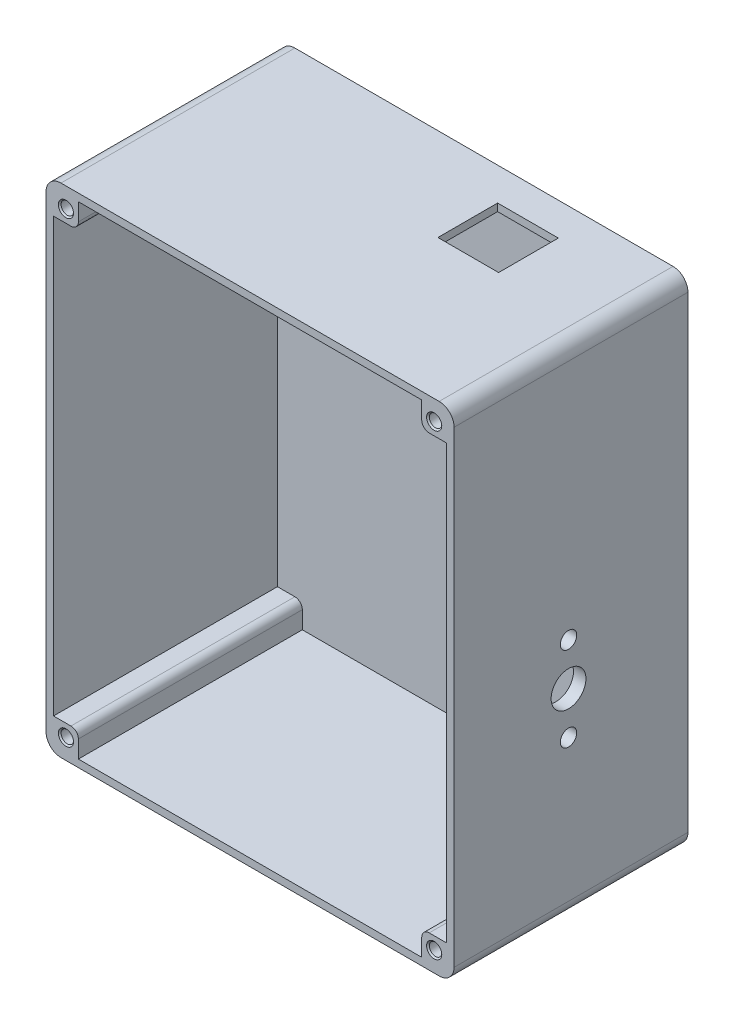
SolidWorks part; units mm, degrees
ref_plane "前视基准面" through (0, 0, 0) normal (0, 0, 1) x (1, 0, 0)
ref_plane "上视基准面" through (0, 0, 0) normal (0, 1, 0) x (1, 0, 0)
ref_plane "右视基准面" through (0, 0, 0) normal (1, 0, 0) x (0, 0, -1)
other "Configuration Table"
sketch "草图2" plane through (0, 0, 0) normal (0, 0, 1) x (1, 0, 0)
  line L1 (0, 0) -> (82, 0)
  line L2 (0, 0) -> (0, -100)
  line L3 (0, -100) -> (82, -100)
  line L4 (82, 0) -> (82, -100)
  dimension "D1" = 82
  dimension "D2" = 100
extrude "凸台-拉伸1" add sketch "草图2" along normal blind 2
sketch "草图9" plane through (0, 0, 2) normal (0, 0, 1) x (1, 0, 0)
  line L0 (0, -50) -> (82, -50) construction
  line L3 (80.5, -6.5) -> (75.5, -6.5)
  line L4 (0, 0) -> (82, 0) construction
  line L5 (82, 0) -> (82, -100) construction
  line L6 (0, -100) -> (82, -100) construction
  line L7 (0, 0) -> (0, -100) construction
  line L8 (80.5, -98.5) -> (80.5, -1.5)
  line L9 (80.5, -1.5) -> (1.5, -1.5)
  line L10 (1.5, -1.5) -> (1.5, -98.5)
  line L11 (1.5, -98.5) -> (80.5, -98.5)
  line L12 (80.5, -93.5) -> (80.5, -6.5)
  line L13 (75.5, -1.5) -> (6.5, -1.5)
  line L14 (1.5, -6.5) -> (1.5, -93.5)
  line L15 (6.5, -98.5) -> (75.5, -98.5)
  line L16 (0, 0) -> (82, 0)
  line L17 (82, 0) -> (82, -100)
  line L18 (0, -100) -> (82, -100)
  line L19 (0, 0) -> (0, -100)
  line L20 (75.5, -1.5) -> (75.5, -6.5)
  line L23 (1.5, -6.5) -> (6.5, -6.5)
  line L24 (6.5, -1.5) -> (6.5, -6.5)
  line L25 (75.5, -98.5) -> (75.5, -93.5)
  line L26 (80.5, -93.5) -> (75.5, -93.5)
  line L27 (6.5, -98.5) -> (6.5, -93.5)
  line L28 (1.5, -93.5) -> (6.5, -93.5)
  dimension "D2" = 5
  dimension "D3" = 5
  dimension "D4" = 5
  dimension "D5" = 5
  dimension "D1" = 1.5
extrude "凸台-拉伸4" add sketch "草图9" along normal blind 45
sketch "草图10" plane through (0, 0, 2) normal (0, 0, 1) x (1, 0, 0)
  line L0 (15, -6) -> (67, -6) construction
  line L1 (75.5, -1.5) -> (6.5, -1.5) construction
  line L2 (75.5, -1.5) -> (6.5, -1.5) construction
  circle A0 centre (15, -6) radius 2.25
  circle A1 centre (67, -6) radius 2.25
  circle A2 centre (67, -38) radius 2.25
  circle A3 centre (15, -38) radius 2.25
  point P2 (41, -6)
  point P11 (41, -1.5)
  dimension "D1" = 4.5
  dimension "D2" = 2
  dimension "D4" = 52
  dimension "D5" = 32
  dimension "D6" = 4.5
  dimension "D3" = 2
extrude "凸台-拉伸5" add sketch "草图10" along normal blind 3
sketch "草图11" plane through (0, 0, 5) normal (0, 0, 1) x (1, 0, 0)
  circle A0 centre (67, -6) radius 2.25 construction
  circle A1 centre (67, -38) radius 2.25 construction
  circle A2 centre (15, -38) radius 2.25 construction
  circle A3 centre (15, -6) radius 2.25 construction
  circle A4 centre (67, -6) radius 2.25
  circle A5 centre (67, -38) radius 2.25
  circle A6 centre (15, -38) radius 2.25
  circle A7 centre (15, -6) radius 2.25
  circle A8 centre (15, -6) radius 1.25
  circle A9 centre (67, -6) radius 1.25
  circle A10 centre (67, -38) radius 1.25
  circle A11 centre (15, -38) radius 1.25
  point P0 (67, -6)
  point P2 (67, -38)
  point P4 (15, -38)
  point P6 (15, -6)
  dimension "D1" = 1
hole_wizard "M3 Tapped Hole1" positions "草图11" profile "草图13" tap size "M3" standard "GB" end condition up to next
cosmetic thread "孔螺纹线1" parameters "D2"=3
cosmetic thread "孔螺纹线2" parameters "D2"=3
cosmetic thread "孔螺纹线3" parameters "D2"=3
cosmetic thread "孔螺纹线4" parameters "D2"=3
sketch "草图13" plane through (67, -6, 5) normal (1, 0, 0) x (0, -1, 0)
  line L0 (0, 0) -> (0, 5)
  line L1 (0, 5) -> (1.25, 5)
  line L2 (1.25, 5) -> (1.25, 0.275)
  line L3 (1.25, 0.275) -> (1.525, 0)
  line L5 (1.525, 0) -> (0, 0)
  line L6 (-1.25, 0.275) -> (-1.525, 0) construction
  line L11 (0, -6.35) -> (0, 107.95) construction
  dimension "Thru Tap Drill Dia." = 2.5
  dimension "Thru Tap Drill Depth" = 5
  dimension "Near C'Sink Dia." = 3.05
  dimension "Near C'Sink Angle" = 90
ref_point "点2"
sketch "草图14" plane through (0, -1.5, 0) normal (0, -1, 0) x (1, 0, 0)
  line L0 (67, 5) -> (67, 23.1936) construction
  line L1 (62.55, 6.6) -> (50.35, 6.6)
  line L2 (62.55, 6.6) -> (62.55, 18.6)
  line L3 (62.55, 18.6) -> (50.35, 18.6)
  line L4 (50.35, 6.6) -> (50.35, 18.6)
  dimension "D1" = 12.2
  dimension "D2" = 12
  dimension "D3" = 4.45
  dimension "D4" = 1.6
extrude "切除-拉伸2" cut sketch "草图14" against normal up to next
sketch "草图16" plane through (82, 0, 0) normal (1, 0, 0) x (0, 0, -1)
  line L0 (-24, -49.191) -> (-24, -71.8515) construction
  line L2 (-30.5809, -60) -> (-18.6896, -60) construction
  line L3 (0, 0) -> (0, -100) construction
  line L4 (-47, 0) -> (0, 0) construction
  circle A0 centre (-24, -60) radius 3.5
  circle A1 centre (-24, -51.5) radius 1.65
  circle A2 centre (-24, -68.5) radius 1.65
  point P5 (-24, -60)
  dimension "D1" = 7
  dimension "D3" = 3.3
  dimension "D4" = 24
  dimension "D2" = 8.5
  dimension "D5" = 60
extrude "切除-拉伸3" cut sketch "草图16" against normal up to next
sketch "草图17" plane through (80.5, 0, 0) normal (-1, 0, 0) x (0, 0, 1)
  line L1 (11, -47) -> (37, -47)
  line L2 (11, -47) -> (11, -73)
  line L3 (11, -73) -> (37, -73)
  line L4 (37, -47) -> (37, -73)
  circle A0 centre (24, -68.5) radius 1.65 construction
  circle A1 centre (24, -60) radius 3.5 construction
  circle A2 centre (24, -51.5) radius 1.65 construction
  circle A3 centre (24, -68.5) radius 1.65
  circle A4 centre (24, -60) radius 3.5
  circle A5 centre (24, -51.5) radius 1.65
  point P13 (37, -60)
  point P15 (24, -60)
  point P16 (24, -47)
  point P17 (24, -51.5)
  circle M2 centre (24, -68.5) radius 1.65
  circle M3 centre (24, -51.5) radius 1.65
  circle M4 centre (24, -60) radius 3.5
  dimension "D1" = 26
  dimension "D2" = 26
extrude "凸台-拉伸6" add sketch "草图17" along normal blind 1 contours L4 L1 L2 L3 M3 M4 M2
sketch "草图20" plane through (0, 0, 47) normal (0, 0, 1) x (1, 0, 0)
  line L10 (0, 0) -> (0, -100) construction
  line L11 (6.5, -6.5) -> (1.5, -6.5) construction
  line L15 (0, -100) -> (82, -100) construction
  point P4 (4, -4)
  point P23 (4, -96)
  point P28 (78, -96)
  point P29 (78, -4)
  dimension "D1" = 4
  dimension "D2" = 2.5
  dimension "D3" = 4
  dimension "D4" = 74
hole_wizard "M3 Tapped Hole3" positions "草图20" profile "草图24" tap size "M3" standard "GB" end condition up to next
sketch "草图24" plane through (4, -4, 47) normal (1, 0, 0) x (0, -1, 0)
  line L0 (0, 0) -> (0, 47)
  line L1 (0, 47) -> (1.25, 47)
  line L2 (1.25, 47) -> (1.25, 0.275)
  line L3 (1.25, 0.275) -> (1.525, 0)
  line L5 (1.525, 0) -> (0, 0)
  line L6 (-1.25, 0.275) -> (-1.525, 0) construction
  line L11 (0, -6.35) -> (0, 107.95) construction
  dimension "Thru Tap Drill Dia." = 2.5
  dimension "Thru Tap Drill Depth" = 47
  dimension "Near C'Sink Dia." = 3.05
  dimension "Near C'Sink Angle" = 90
cosmetic thread "孔螺纹线5" parameters "D2"=3
cosmetic thread "孔螺纹线6" parameters "D2"=3
cosmetic thread "孔螺纹线7" parameters "D2"=3
cosmetic thread "孔螺纹线8" parameters "D2"=3
fillet "圆角2" radius 3 4 edges at (0, 0, 23.5) (82, 0, 23.5) (82, -100, 23.5) (0, -100, 23.5)
fillet "圆角3" radius 1.5 4 edges at (75.5, -93.5, 24.5) (75.5, -6.5, 24.5) (6.5, -6.5, 24.5) (6.5, -93.5, 24.5)
